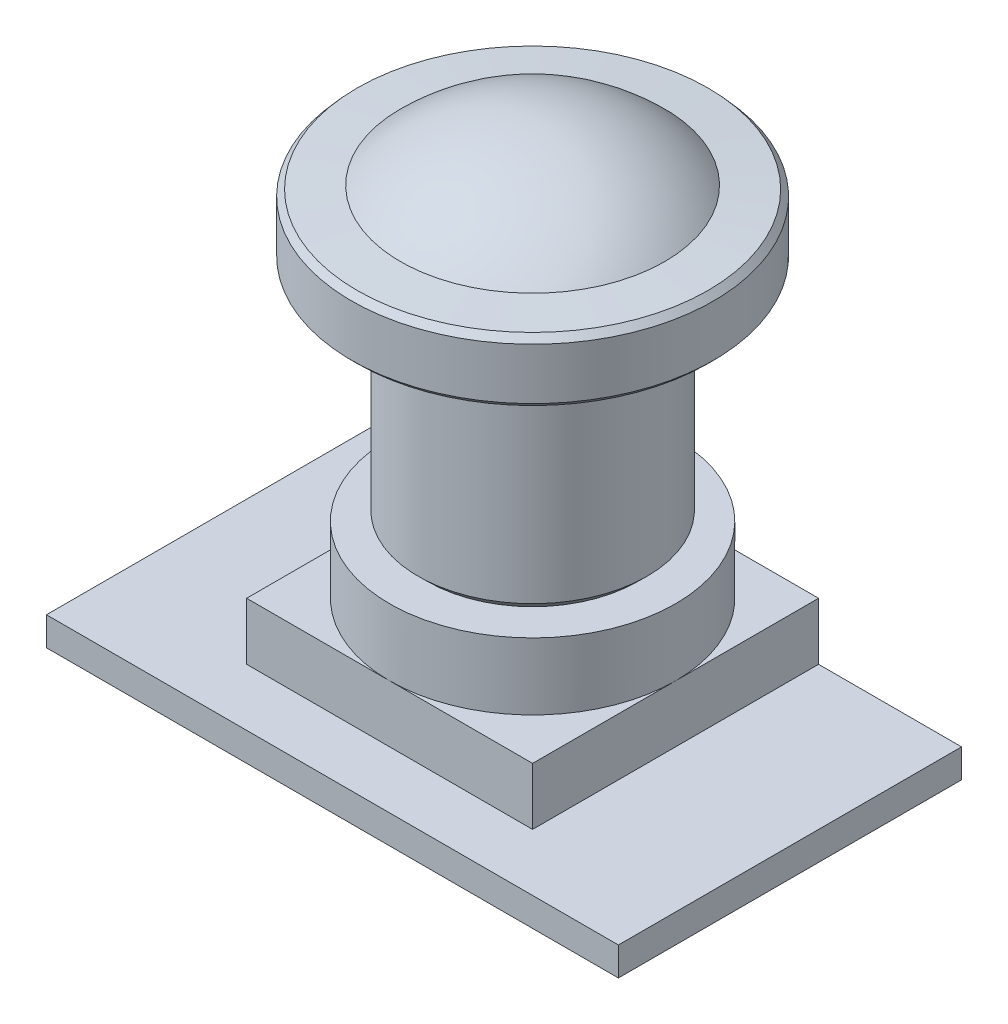
SolidWorks part; units mm, degrees
material "SUNTR"
ref_plane "Front Plane" through (0, 0, 0) normal (0, 0, 1) x (1, 0, 0)
ref_plane "Top Plane" through (0, 0, 0) normal (0, 1, 0) x (1, 0, 0)
ref_plane "Right Plane" through (0, 0, 0) normal (1, 0, 0) x (0, 0, -1)
sketch "Model" plane through (0, 0, 0) normal (0, 0, 1) x (1, 0, 0)
  line L25 (35.5656, 69.9037) -> (35.5656, 2.4157)
  line L430 (13.1823, 43.6481) -> (13.1823, 4.2595)
  line L431 (0.1488, 57.4368) -> (0.1488, 47.3812)
  line L432 (9.7015, 59.3306) -> (1.2457, 58.6659)
  line L433 (1.2457, 58.6659) -> (0.1488, 57.4368)
  line L434 (2.9573, 46.2387) -> (1.2898, 46.2387)
  line L435 (1.2898, 46.2387) -> (0.1488, 47.3812)
  line L436 (14.1483, 44.5699) -> (15.0703, 44.5699)
  line L437 (15.0703, 46.2387) -> (15.0703, 44.5699)
  line L438 (14.1483, 44.5699) -> (13.1823, 43.6481)
  line L439 (35.5656, 2.4157) -> (15.0703, 2.4157)
  line L440 (15.0703, 2.4157) -> (13.1823, 4.2595)
  line L444 (2.9573, 46.2387) -> (15.0703, 46.2387)
  arc A0 (35.5656, 69.9037) -> (9.7015, 59.3306) centre (35.4978, 33.1487) ccw
revolve "Revolve1" add sketch "Model" angle 360 about L25
scale "Scale1" scale about centroid uniform scaling yes scale factor 0.26809
sketch "Sketch2" plane through (0, 29.0113, 0) normal (0, -1, 0) x (1, 0, 0)
  circle A0 centre (35.5656, 0) radius 7.5
  dimension "D1" = 15
extrude "Boss-Extrude1" add sketch "Sketch2" along normal blind 3.5
sketch "Sketch3" plane through (0, 25.5113, 0) normal (0, -1, 0) x (1, 0, 0)
  line L1 (28.0656, 7.5) -> (43.0656, 7.5)
  line L2 (28.0656, 7.5) -> (28.0656, -7.5)
  line L3 (28.0656, -7.5) -> (43.0656, -7.5)
  line L4 (43.0656, 7.5) -> (43.0656, -7.5)
  line L5 (28.0656, 7.5) -> (43.0656, -7.5) construction
  line L6 (28.0656, -7.5) -> (43.0656, 7.5) construction
  point P0 (35.5656, 0)
  dimension "D1" = 15
  dimension "D2" = 15
extrude "Boss-Extrude2" add sketch "Sketch3" along normal blind 3
sketch "Sketch4" plane through (0, 22.5113, 0) normal (0, -1, 0) x (1, 0, 0)
  line L0 (28.0656, -7.5) -> (43.0656, -7.5) construction
  line L1 (50.5656, -7.5) -> (20.5656, -7.5)
  line L2 (50.5656, -7.5) -> (50.5656, 10.5)
  line L3 (50.5656, 10.5) -> (20.5656, 10.5)
  line L4 (20.5656, -7.5) -> (20.5656, 10.5)
  line L5 (35.5656, 7.5) -> (35.5656, -13.9292) construction
  line L6 (43.0656, 7.5) -> (28.0656, 7.5) construction
  dimension "D1" = 18
  dimension "D2" = 15
  dimension "D3" = 30
extrude "Boss-Extrude3" add sketch "Sketch4" along normal blind 1.5
